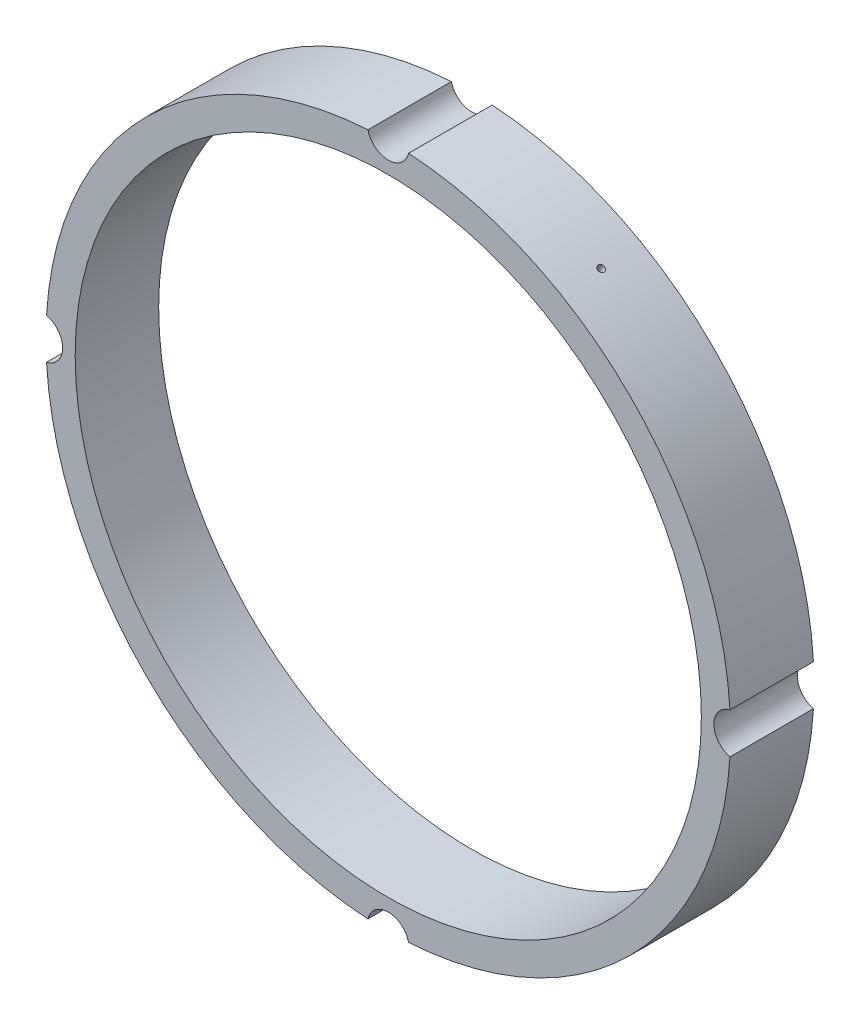
SolidWorks part; units mm, degrees
ref_plane "Front Plane" through (0, 0, 0) normal (0, 0, 1) x (1, 0, 0)
ref_plane "Top Plane" through (0, 0, 0) normal (0, 1, 0) x (1, 0, 0)
ref_plane "Right Plane" through (0, 0, 0) normal (1, 0, 0) x (0, 0, -1)
sketch "Sketch1" plane through (0, 0, 0) normal (0, 0, 1) x (1, 0, 0)
  circle A0 centre (0, 0) radius 75
  circle A1 centre (0, 0) radius 82
extrude "Boss-Extrude1" add sketch "Sketch1" along normal blind 20
sketch "Sketch2" plane through (0, 0, 20) normal (0, 0, 1) x (1, 0, 0)
  circle A0 centre (0, 83) radius 5
extrude "Cut-Extrude1" cut sketch "Sketch2" against normal through all
pattern_circular "CirPattern1" count 4 every 90 about axis through (0, 0, 0) along (0, 0, 1) of "Cut-Extrude1"
hole_wizard "M2x0.4 Tapped Hole1" positions "3DSketch1" profile "Sketch3" tap size "M2x0.4" standard "ANSI Metric"
sketch3d "3DSketch1"
  point P0 (41, 71.0141, 10)
sketch "Sketch3" plane through (41, 71.0141, 10) normal (0, 0, 1) x (-0.866, 0.5, 0)
  line L0 (0, 0) -> (0, 10.4807)
  line L1 (0, 10.4807) -> (0.8, 10)
  line L2 (0.8, 10) -> (0.8, 0)
  line L5 (0.8, 0) -> (0, 0)
  line L10 (0, 10.4807) -> (-0.8, 10) construction
  line L11 (0, -6.35) -> (0, 107.95) construction
  dimension "Tap Drill Dia." = 1.6
  dimension "Tap Drill Depth" = 10
  dimension "Drill Angle" = 118
cosmetic thread "Hole Thread1" parameters "D1"=4, "D2"=2
